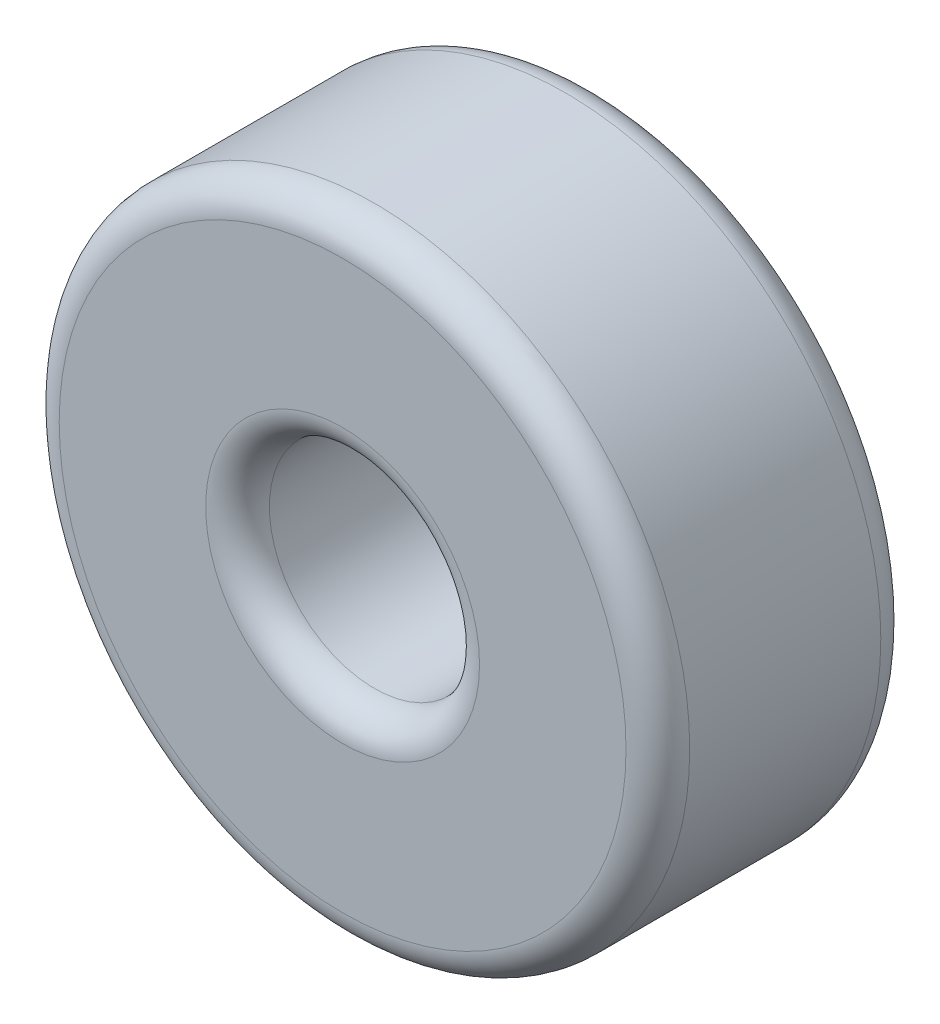
SolidWorks part; units mm, degrees
ref_plane "Спереди" through (0, 0, 0) normal (0, 0, 1) x (1, 0, 0)
ref_plane "Сверху" through (0, 0, 0) normal (0, 1, 0) x (1, 0, 0)
ref_plane "Справа" through (0, 0, 0) normal (1, 0, 0) x (0, 0, -1)
sketch "Эскиз1" plane through (0, 0, 0) normal (0, 0, 1) x (1, 0, 0)
  circle A0 centre (0, 0) radius 1.65
  circle A1 centre (0, 0) radius 4.95
  dimension "D1" = 3.3
  dimension "D2" = 9.9
extrude "Бобышка-Вытянуть1" add sketch "Эскиз1" along normal blind 4
fillet "Скругление1" radius 0.5 4 edges at (1.65, 0, 0) (4.95, 0, 0) (1.65, 0, 4) (4.95, 0, 4)
